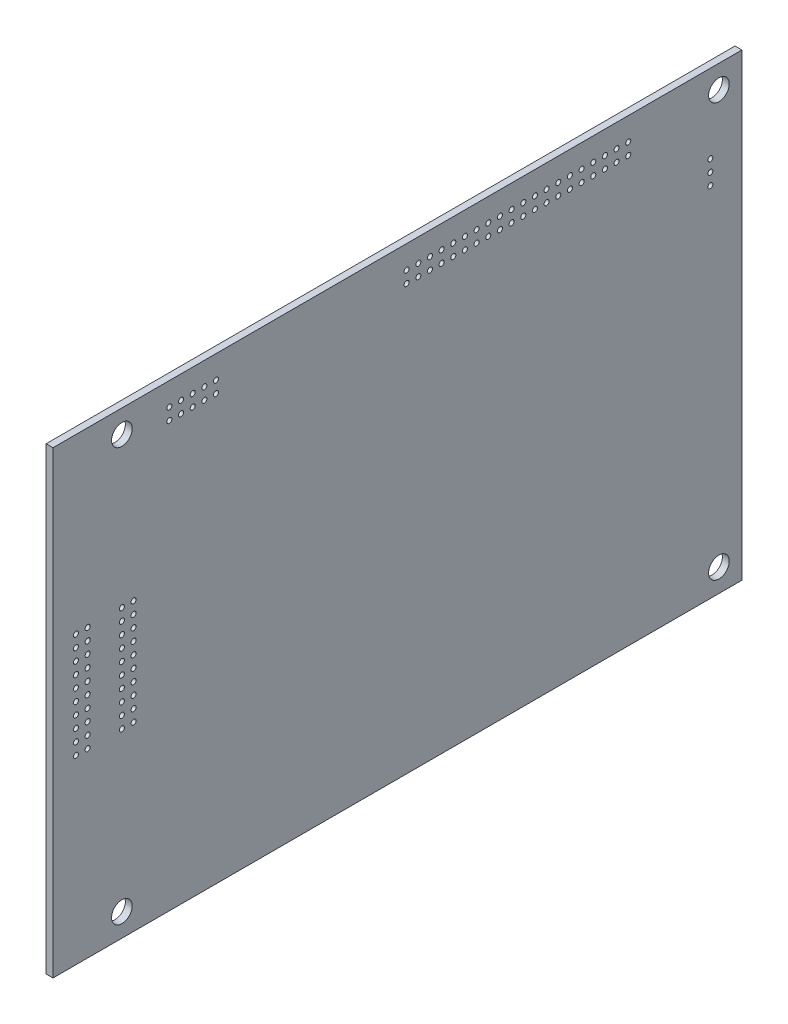
SolidWorks part; units mm, degrees
ref_plane "Спереди" through (0, 0, 0) normal (0, 0, 1) x (1, 0, 0)
ref_plane "Сверху" through (0, 0, 0) normal (0, 1, 0) x (1, 0, 0)
ref_plane "Справа" through (0, 0, 0) normal (1, 0, 0) x (0, 0, -1)
sketch "Эскиз1" plane through (0, 0, 0) normal (1, 0, 0) x (0, 0, -1)
  line L0 (-25.6582, 0) -> (27.1184, 0) construction
  line L2 (-75, -50) -> (75, -50)
  line L3 (-75, -50) -> (-75, 50)
  line L4 (-75, 50) -> (75, 50)
  line L5 (75, -50) -> (75, 50)
  circle A0 centre (-60, 45) radius 2.25
  circle A1 centre (-60, -45) radius 2.25
  circle A2 centre (70, -45) radius 2.25
  circle A3 centre (70, 45) radius 2.25
  dimension "D3" = 5
  dimension "D5" = 130
  dimension "D6" = 5
  dimension "D7" = 4.5
  dimension "D4" = 130
  dimension "D8" = 5
  dimension "D1" = 150
  dimension "D2" = 100
extrude "Вытянуть1" add sketch "Эскиз1" along normal blind 1.5
sketch "Эскиз2" plane through (1.5, 0, 0) normal (1, 0, 0) x (0, 0, -1)
  line L0 (-75, 50) -> (-75, -50) construction
  line L1 (-75, -50) -> (75, -50) construction
  line L2 (68.125, 27.835) -> (68.125, 29.336) construction
  circle A0 centre (-70, 12.335) radius 0.55
  circle A1 centre (-67.46, 12.335) radius 0.55
  circle A2 centre (-70, 9.795) radius 0.55
  circle A3 centre (-67.46, 9.795) radius 0.55
  circle A4 centre (-70, 7.255) radius 0.55
  circle A5 centre (-67.46, 7.255) radius 0.55
  circle A6 centre (-70, 4.715) radius 0.55
  circle A7 centre (-67.46, 4.715) radius 0.55
  circle A8 centre (-70, 2.175) radius 0.55
  circle A9 centre (-67.46, 2.175) radius 0.55
  circle A10 centre (-70, -0.365) radius 0.55
  circle A11 centre (-67.46, -0.365) radius 0.55
  circle A12 centre (-70, -2.905) radius 0.55
  circle A13 centre (-67.46, -2.905) radius 0.55
  circle A14 centre (-70, -5.445) radius 0.55
  circle A15 centre (-67.46, -5.445) radius 0.55
  circle A16 centre (-70, -7.985) radius 0.55
  circle A17 centre (-67.46, -7.985) radius 0.55
  circle A18 centre (-70, -10.525) radius 0.55
  circle A19 centre (-67.46, -10.525) radius 0.55
  circle A20 centre (-49.66, 45) radius 0.55
  circle A21 centre (-49.66, 42.46) radius 0.55
  circle A22 centre (-47.12, 45) radius 0.55
  circle A23 centre (-47.12, 42.46) radius 0.55
  circle A24 centre (-44.58, 45) radius 0.55
  circle A25 centre (-44.58, 42.46) radius 0.55
  circle A26 centre (-42.04, 45) radius 0.55
  circle A27 centre (-42.04, 42.46) radius 0.55
  circle A28 centre (-39.5, 45) radius 0.55
  circle A29 centre (-39.5, 42.46) radius 0.55
  circle A30 centre (2, 45) radius 0.55
  circle A31 centre (2, 42.46) radius 0.55
  circle A32 centre (4.54, 45) radius 0.55
  circle A33 centre (4.54, 42.46) radius 0.55
  circle A34 centre (7.08, 45) radius 0.55
  circle A35 centre (7.08, 42.46) radius 0.55
  circle A36 centre (9.62, 45) radius 0.55
  circle A37 centre (9.62, 42.46) radius 0.55
  circle A38 centre (12.16, 45) radius 0.55
  circle A39 centre (12.16, 42.46) radius 0.55
  circle A40 centre (14.7, 45) radius 0.55
  circle A41 centre (14.7, 42.46) radius 0.55
  circle A42 centre (17.24, 45) radius 0.55
  circle A43 centre (17.24, 42.46) radius 0.55
  circle A44 centre (19.78, 45) radius 0.55
  circle A45 centre (19.78, 42.46) radius 0.55
  circle A46 centre (22.32, 45) radius 0.55
  circle A47 centre (22.32, 42.46) radius 0.55
  circle A48 centre (24.86, 45) radius 0.55
  circle A49 centre (24.86, 42.46) radius 0.55
  circle A50 centre (27.4, 45) radius 0.55
  circle A51 centre (27.4, 42.46) radius 0.55
  circle A52 centre (29.94, 45) radius 0.55
  circle A53 centre (29.94, 42.46) radius 0.55
  circle A54 centre (32.48, 45) radius 0.55
  circle A55 centre (32.48, 42.46) radius 0.55
  circle A56 centre (35.02, 45) radius 0.55
  circle A57 centre (35.02, 42.46) radius 0.55
  circle A58 centre (37.56, 45) radius 0.55
  circle A59 centre (37.56, 42.46) radius 0.55
  circle A60 centre (40.1, 45) radius 0.55
  circle A61 centre (40.1, 42.46) radius 0.55
  circle A62 centre (42.64, 45) radius 0.55
  circle A63 centre (42.64, 42.46) radius 0.55
  circle A64 centre (45.18, 45) radius 0.55
  circle A65 centre (45.18, 42.46) radius 0.55
  circle A66 centre (47.72, 45) radius 0.55
  circle A67 centre (47.72, 42.46) radius 0.55
  circle A68 centre (50.26, 45) radius 0.55
  circle A69 centre (50.26, 42.46) radius 0.55
  circle A70 centre (68.125, 32.915) radius 0.55
  circle A71 centre (68.125, 30.375) radius 0.55
  circle A72 centre (68.125, 27.835) radius 0.55
  circle A73 centre (-60, 12.335) radius 0.55
  circle A74 centre (-57.46, 12.335) radius 0.55
  circle A75 centre (-60, 9.795) radius 0.55
  circle A76 centre (-57.46, 9.795) radius 0.55
  circle A77 centre (-60, 7.255) radius 0.55
  circle A78 centre (-57.46, 7.255) radius 0.55
  circle A79 centre (-60, 4.715) radius 0.55
  circle A80 centre (-57.46, 4.715) radius 0.55
  circle A81 centre (-60, 2.175) radius 0.55
  circle A82 centre (-57.46, 2.175) radius 0.55
  circle A83 centre (-60, -0.365) radius 0.55
  circle A84 centre (-57.46, -0.365) radius 0.55
  circle A85 centre (-60, -2.905) radius 0.55
  circle A86 centre (-57.46, -2.905) radius 0.55
  circle A87 centre (-60, -5.445) radius 0.55
  circle A88 centre (-57.46, -5.445) radius 0.55
  circle A89 centre (-60, -7.985) radius 0.55
  circle A90 centre (-57.46, -7.985) radius 0.55
  circle A91 centre (-60, -10.525) radius 0.55
  circle A92 centre (-57.46, -10.525) radius 0.55
  dimension "D1" = 1.1
  dimension "D4" = 2.54
  dimension "D8" = 1.1
  dimension "D10" = 2.54
  dimension "D13" = 2.54
  dimension "D17" = 2.54
  dimension "D18" = 2.54
  dimension "D2" = 5
  dimension "D3" = 62.335
  dimension "D5" = 62.335
  dimension "D6" = 25.34
  dimension "D7" = 95
  dimension "D9" = 25.34
  dimension "D11" = 77
  dimension "D12" = 95
  dimension "D14" = 77
  dimension "D15" = 143.125
  dimension "D16" = 82.915
extrude "Вырез-Вытянуть1" cut sketch "Эскиз2" against normal blind 10
